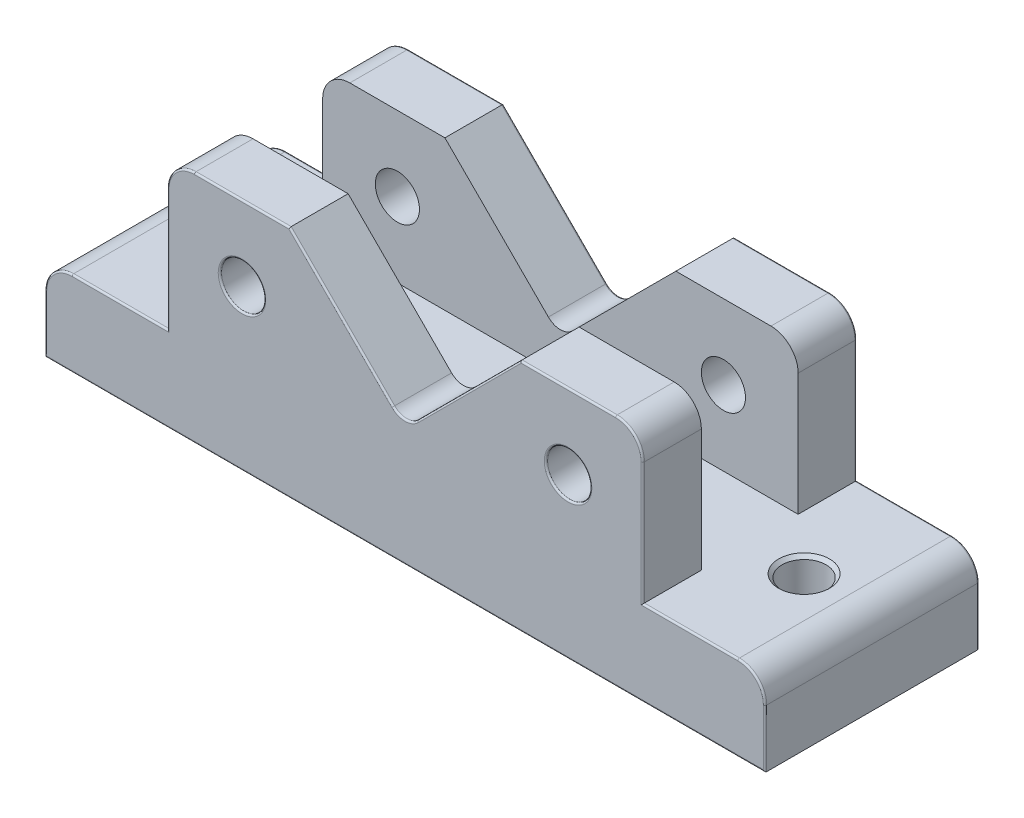
SolidWorks part; units mm, degrees
ref_plane "Front Plane" through (0, 0, 0) normal (0, 0, 1) x (1, 0, 0)
ref_plane "Top Plane" through (0, 0, 0) normal (0, 1, 0) x (1, 0, 0)
ref_plane "Right Plane" through (0, 0, 0) normal (1, 0, 0) x (0, 0, -1)
sketch "Sketch1" plane through (0, 0, 0) normal (0, 0, 1) x (1, 0, 0)
  line L0 (0, 0) -> (0, 50) construction
  line L1 (0, 0) -> (212, 0)
  line L2 (0, 0) -> (0, 17)
  line L3 (8, 25) -> (36, 25)
  line L4 (36, 25) -> (36, 61)
  line L5 (44, 69) -> (72, 69)
  line L6 (72, 69) -> (102.4645, 38.5355)
  line L7 (106, 0) -> (106, 77.8647) construction
  line L8 (212, 0) -> (212, 50) construction
  line L9 (140, 69) -> (109.5355, 38.5355)
  line L10 (168, 69) -> (140, 69)
  line L11 (176, 25) -> (176, 61)
  line L12 (204, 25) -> (176, 25)
  line L13 (212, 0) -> (212, 17)
  arc A0 (44, 69) -> (36, 61) centre (44, 61) ccw
  arc A1 (0, 17) -> (8, 25) centre (8, 17) cw
  arc A2 (212, 17) -> (204, 25) centre (204, 17) ccw
  arc A3 (168, 69) -> (176, 61) centre (168, 61) cw
  arc A4 (109.5355, 38.5355) -> (102.4645, 38.5355) centre (106, 42.0711) cw
  point P12 (36, 69)
  point P15 (0, 25)
  point P26 (212, 25)
  point P27 (176, 69)
  point P30 (106, 35)
  dimension "D7" = 8
  dimension "D8" = 5
  dimension "D1" = 25
  dimension "D2" = 36
  dimension "D3" = 44
  dimension "D4" = 36
  dimension "D5" = 45
  dimension "D6" = 34
extrude "Boss-Extrude1" add sketch "Sketch1" along normal mid plane 63
sketch "Sketch2" plane through (176, 0, 0) normal (1, 0, 0) x (0, 0, -1)
  line L0 (-31.5, 25) -> (31.5, 25) construction
  line L1 (-14.25, 25) -> (14.25, 25)
  line L2 (-14.25, 25) -> (-14.25, 69)
  line L3 (-14.25, 69) -> (14.25, 69)
  line L4 (14.25, 25) -> (14.25, 69)
  line L5 (-31.5, 69) -> (31.5, 69) construction
  line L6 (-14.25, 69) -> (14.25, 25) construction
  line L7 (14.25, 69) -> (-14.25, 25) construction
  line L8 (0, 0) -> (0, 47) construction
  dimension "D1" = 28.5
extrude "Cut-Extrude1" cut sketch "Sketch2" against normal up to surface (140 mm away) up to face at (36, 43, 0)
sketch "Sketch3" plane through (0, 0, 31.5) normal (0, 0, 1) x (1, 0, 0)
  line L0 (106, 0) -> (106, 87.9684) construction
  line L1 (0, 0) -> (212, 0) construction
  line L2 (72, 69) -> (44, 69) construction
  circle A0 centre (58, 47) radius 6.5
  circle A1 centre (154, 47) radius 6.5
  dimension "D2" = 13
  dimension "D1" = 48
  dimension "D3" = 22
extrude "Cut-Extrude2" cut sketch "Sketch3" against normal through all
sketch "Sketch4" plane through (0, 25, 0) normal (0, 1, 0) x (1, 0, 0)
  line L0 (0, 0) -> (212, 0) construction
  line L1 (212, -31.5) -> (212, 31.5) construction
  line L2 (0, -31.5) -> (0, 31.5) construction
  circle A0 centre (20, 0) radius 6.5
  circle A1 centre (192, 0) radius 6.5
  dimension "D1" = 13
  dimension "D3" = 13
  dimension "D4" = 20
  dimension "D2" = 20
extrude "Cut-Extrude3" cut sketch "Sketch4" against normal through all
fillet "Fillet1" radius 0.5 36 edges at (106, 0, -31.5) (212, 8.5, -31.5) (209.6569, 22.6569, -31.5) (190, 25, -31.5) (176, 43, -31.5) (173.6569, 66.6569, -31.5) (154, 69, -31.5) (124.7678, 53.7678, -31.5) (106, 37.0711, -31.5) (87.2322, 53.7678, -31.5) (58, 69, -31.5) (38.3431, 66.6569, -31.5) (36, 43, -31.5) (22, 25, -31.5) (2.3431, 22.6569, -31.5) (0, 8.5, -31.5) (147.5, 47, -31.5) (64.5, 47, -31.5) (2.3431, 22.6569, 31.5) (22, 25, 31.5) (36, 43, 31.5) (38.3431, 66.6569, 31.5) (58, 69, 31.5) (87.2322, 53.7678, 31.5) (106, 37.0711, 31.5) (124.7678, 53.7678, 31.5) (154, 69, 31.5) (173.6569, 66.6569, 31.5) (176, 43, 31.5) (190, 25, 31.5) (209.6569, 22.6569, 31.5) (212, 8.5, 31.5) (106, 0, 31.5) (0, 8.5, 31.5) (147.5, 47, 31.5) (64.5, 47, 31.5)
chamfer "Chamfer1" distance 1 angle 45 2 edges at (192, 25, 6.5) (20, 25, 6.5)
